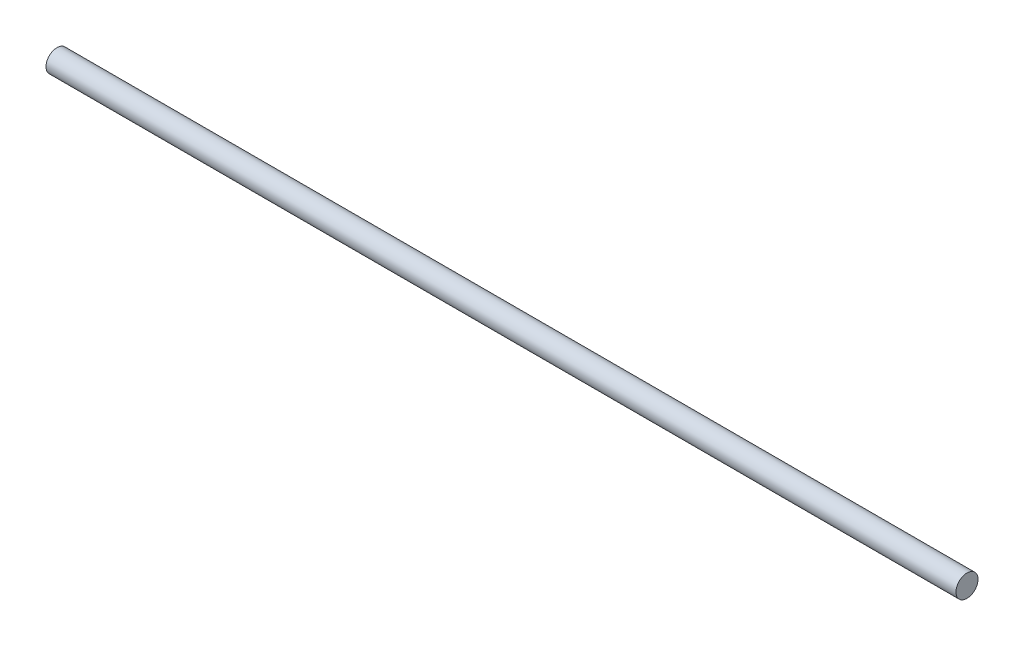
SolidWorks part; units mm, degrees
ref_plane "Front Plane" through (0, 0, 0) normal (0, 0, 1) x (1, 0, 0)
ref_plane "Top Plane" through (0, 0, 0) normal (0, 1, 0) x (1, 0, 0)
ref_plane "Right Plane" through (0, 0, 0) normal (1, 0, 0) x (0, 0, -1)
sketch "Sketch1" plane through (34.8052, 0, 0) normal (1, 0, 0) x (0, 0, -1)
  circle A0 centre (-18.4449, -14.0193) radius 4 construction
  circle A1 centre (-18.4449, -14.0193) radius 4
extrude "Boss-Extrude2" add sketch "Sketch1" along normal blind 330
